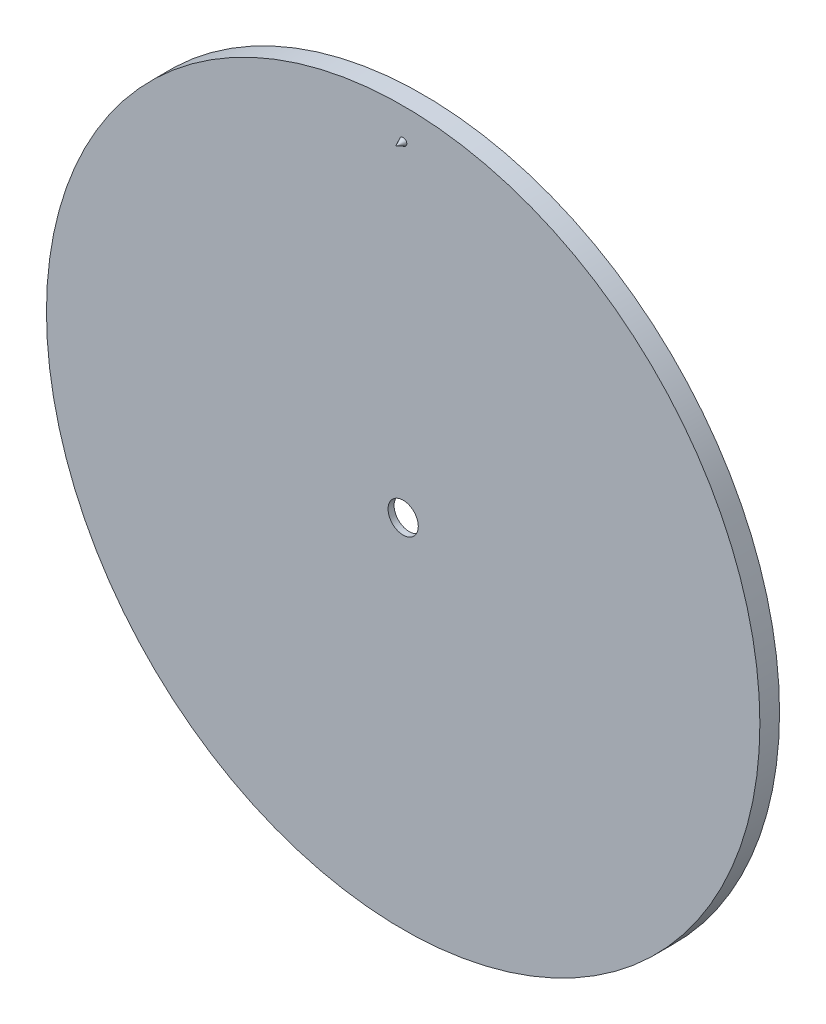
SolidWorks part; units mm, degrees
ref_plane "Front Plane" through (0, 0, 0) normal (0, 0, 1) x (1, 0, 0)
ref_plane "Top Plane" through (0, 0, 0) normal (0, 1, 0) x (1, 0, 0)
ref_plane "Right Plane" through (0, 0, 0) normal (1, 0, 0) x (0, 0, -1)
sketch "Sketch1" plane through (0, 0, 0) normal (0, 0, 1) x (1, 0, 0)
  circle A0 centre (0, 0) radius 74.93
  circle A1 centre (0, 0) radius 3.175
  dimension "D1" = 149.86
  dimension "D2" = 6.35
extrude "Boss-Extrude1" add sketch "Sketch1" along normal blind 4.1275
sketch "Sketch2" plane through (0, 0, 0) normal (0, 0, -1) x (-1, 0, 0)
  circle A0 centre (0, 0) radius 73.66
  dimension "D1" = 147.32
extrude "Cut-Extrude1" cut sketch "Sketch2" against normal blind 2.8575
sketch "Sketch3" plane through (0, 0, 0) normal (1, 0, 0) x (0, 0, -1)
  line L0 (-5.6515, 68.4004) -> (-4.1275, 68.4004) construction
  line L1 (-4.1275, 74.93) -> (-4.1275, -74.93) construction
  line L2 (-5.6515, 68.4004) -> (-4.1275, 69.1624)
  line L3 (-4.1275, 69.1624) -> (-4.1275, 68.4004)
  line L4 (-5.6515, 68.4004) -> (-4.1275, 68.4004)
  dimension "D1" = 1.524
  dimension "D2" = 0.762
revolve "Revolve1" add sketch "Sketch3" angle 360 about L0
pattern_linear "LPattern1" [suppressed] count 6 spacing 10.16
